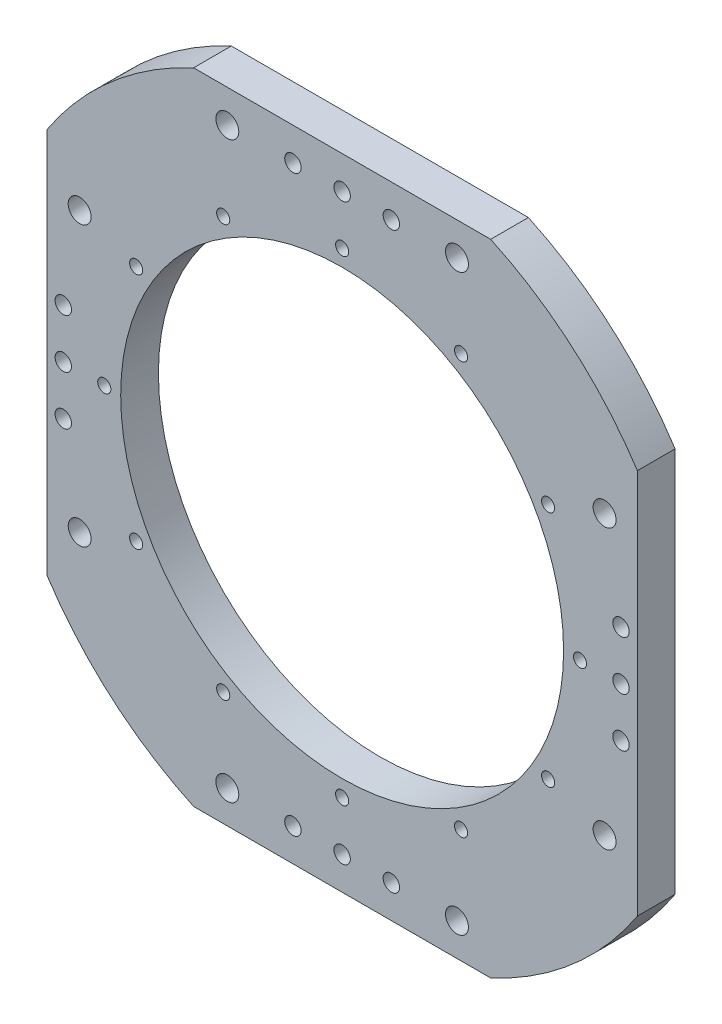
SolidWorks part; units mm, degrees
ref_plane "前视基准面" through (0, 0, 0) normal (0, 0, 1) x (1, 0, 0)
ref_plane "上视基准面" through (0, 0, 0) normal (0, 1, 0) x (1, 0, 0)
ref_plane "右视基准面" through (0, 0, 0) normal (1, 0, 0) x (0, 0, -1)
sketch "草图1" plane through (0, 0, 0) normal (0, 0, 1) x (1, 0, 0)
  line L1 (-200, 200) -> (160, 200)
  line L2 (-200, 200) -> (-200, -190)
  line L3 (-200, -190) -> (160, -190)
  line L4 (160, 200) -> (160, -190)
  dimension "D1" = 390
  dimension "D2" = 360
extrude "拉伸1" add sketch "草图1" along normal blind 23
sketch "草图2" plane through (0, 0, 23) normal (0, 0, 1) x (1, 0, 0)
  line L0 (160, 200) -> (-200, 200) construction
  circle A0 centre (-20, 5) radius 135
  dimension "D1" = 270
  dimension "D2" = 195
extrude "切除-拉伸1" cut sketch "草图2" against normal blind 30
chamfer "倒角1" distance 20 angle 45 4 edges at (-200, -190, 11.5) (160, -190, 11.5) (160, 200, 11.5) (-200, 200, 11.5)
sketch "草图5" plane through (0, 0, 23) normal (0, 0, 1) x (1, 0, 0)
  circle A0 centre (52.5, 130.5737) radius 4
  circle A1 centre (-20, 150) radius 4
  circle A2 centre (105.5737, 77.5) radius 4
  circle A3 centre (125, 5) radius 4
  circle A4 centre (105.5737, -67.5) radius 4
  circle A5 centre (52.5, -120.5737) radius 4
  circle A6 centre (-20, -140) radius 4
  circle A7 centre (-92.5, -120.5737) radius 4
  circle A8 centre (-145.5737, -67.5) radius 4
  circle A9 centre (-165, 5) radius 4
  circle A10 centre (-145.5737, 77.5) radius 4
  circle A11 centre (-92.5, 130.5737) radius 4
  dimension "D1" = 8
extrude "切除-拉伸2" cut sketch "草图5" against normal blind 35
sketch "草图6" plane through (0, 0, 23) normal (0, 0, 1) x (1, 0, 0)
  line L0 (-180, -190) -> (140, -190) construction
  line L2 (140, 200) -> (-180, 200) construction
  circle A0 centre (140, -80) radius 7
  circle A1 centre (50, 180) radius 7
  circle A2 centre (140, -155) radius 7
  circle A3 centre (-90, 180) radius 7
  circle A4 centre (140, 165) radius 7
  circle A5 centre (140, 90) radius 7
  circle A6 centre (50, -170) radius 7
  circle A8 centre (-90, -170) radius 7
  circle A9 centre (-180, 90) radius 7
  circle A12 centre (-180, 165) radius 7
  circle A13 centre (-180, -155) radius 7
  circle A14 centre (-180, -80) radius 7
  circle A20 centre (-20, 180) radius 7 [skipped]
  circle A24 centre (-160, 180) radius 7 [skipped]
  circle A27 centre (120, 180) radius 7 [skipped]
  dimension "D1" = 320
  dimension "D2" = 35
  dimension "D5" = 35
  dimension "D6" = 140
  dimension "D7" = 140
  dimension "D8" = 20
  dimension "D9" = 20
  dimension "D10" = 14
  dimension "D11" = 14
  dimension "D12" = 14
  dimension "D13" = 14
  dimension "D14" = 14
  dimension "D15" = 14
  dimension "D16" = 14
  dimension "D17" = 14
  dimension "D18" = 14
  dimension "D19" = 14
extrude "切除-拉伸3" cut sketch "草图6" against normal blind 35
sketch "草图11" plane through (0, 0, 23) normal (0, 0, 1) x (1, 0, 0)
  circle A0 centre (-20, 5) radius 215
  dimension "D1" = 430
extrude "切除-拉伸8" cut sketch "草图11" against normal through all flip side to cut
sketch "草图12" plane through (0, 0, 23) normal (0, 0, 1) x (1, 0, 0)
  circle A0 centre (-50, 180) radius 5
  circle A1 centre (10, 180) radius 5
  circle A2 centre (-90, 180) radius 7 construction
  circle A3 centre (50, 180) radius 7 construction
  circle A5 centre (10, -170) radius 5
  circle A6 centre (-50, -170) radius 5
  dimension "D1" = 10
  dimension "D2" = 10
  dimension "D3" = 40
  dimension "D4" = 40
  dimension "D5" = 10
  dimension "D6" = 10
extrude "切除-拉伸9" cut sketch "草图12" against normal blind 28
sketch "草图13" plane through (0, 0, 23) normal (0, 0, 1) x (1, 0, 0)
  circle A0 centre (-20, 180) radius 5
  circle A1 centre (-20, -170) radius 5
  dimension "D1" = 10
  dimension "D2" = 10
extrude "切除-拉伸10" cut sketch "草图13" against normal through all
sketch "草图15" plane through (0, 0, 23) normal (0, 0, 1) x (1, 0, 0)
  line L0 (160, -112.5798) -> (160, 122.5798) construction
  line L2 (-200, 122.5798) -> (-200, -112.5798) construction
  circle A0 centre (-190, 35) radius 5
  circle A3 centre (150, -25) radius 5
  circle A5 centre (-190, 5) radius 5
  circle A6 centre (-190, -25) radius 5
  circle A7 centre (150, 5) radius 5
  circle A8 centre (150, 35) radius 5
  dimension "D1" = 10
  dimension "D3" = 10
  dimension "D4" = 10
  dimension "D5" = 10
  dimension "D6" = 10
  dimension "D7" = 10
  dimension "D8" = 10
  dimension "D9" = 10
  dimension "D10" = 30
  dimension "D11" = 30
  dimension "D13" = 30
extrude "切除-拉伸11" cut sketch "草图15" against normal blind 28
